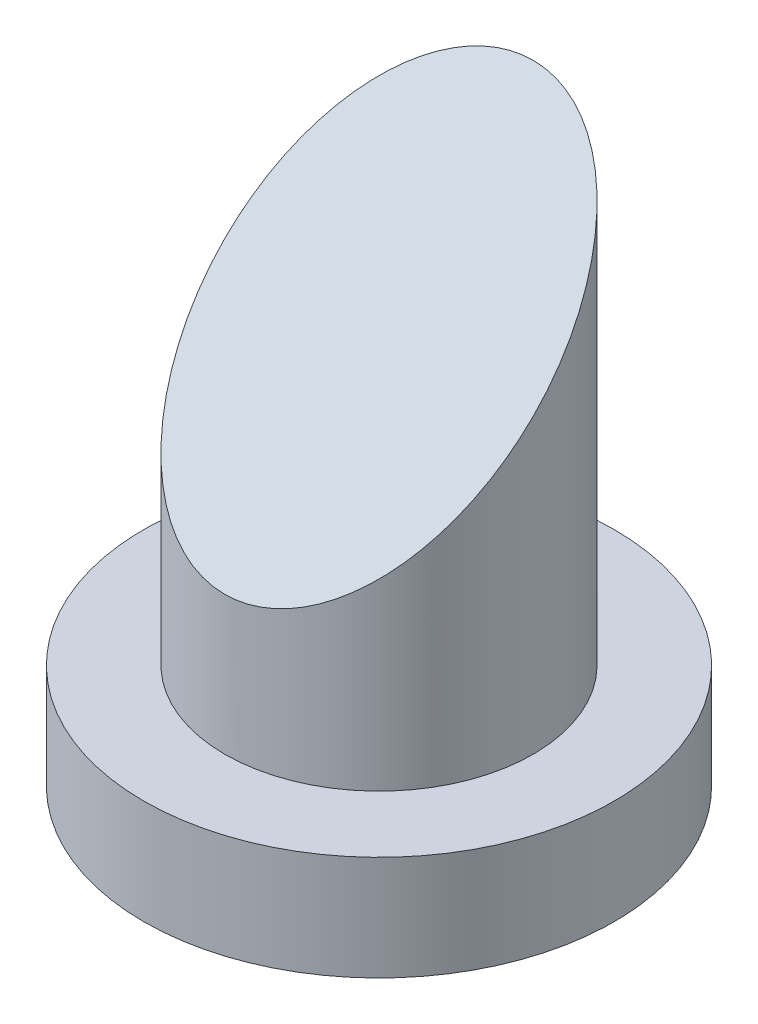
SolidWorks part; units mm, degrees
material "PTFE (general)"
ref_plane "Front Plane" through (0, 0, 0) normal (0, 0, 1) x (1, 0, 0)
ref_plane "Top Plane" through (0, 0, 0) normal (0, 1, 0) x (1, 0, 0)
ref_plane "Right Plane" through (0, 0, 0) normal (1, 0, 0) x (0, 0, -1)
sketch "Sketch1" plane through (0, 0, 0) normal (0, 1, 0) x (1, 0, 0)
  circle A0 centre (0, 0) radius 9
  dimension "D1" = 18
extrude "Boss-Extrude1" add sketch "Sketch1" along normal blind 4
sketch "Sketch2" plane through (0, 4, 0) normal (0, 1, 0) x (1, 0, 0)
  circle A0 centre (0, 0) radius 5.9
  dimension "D1" = 11.8
extrude "Boss-Extrude2" add sketch "Sketch2" along normal blind 20
sketch "Sketch3" plane through (0, 0, 0) normal (1, 0, 0) x (0, 0, -1)
  line L0 (-6.28, 8.92) -> (6.28, 21.48)
  line L2 (9, 4) -> (-9, 4) construction
  line L4 (-6.28, 8.92) -> (-6.28, 28.7719)
  line L5 (-6.28, 28.7719) -> (6.28, 28.7719)
  line L6 (6.28, 21.48) -> (6.28, 28.7719)
  point P2 (0, 15.2)
  dimension "D1" = 12.56
  dimension "D2" = 45
  dimension "D3" = 12.56
  dimension "D4" = 6.28
  dimension "D5" = 11.2
extrude "Cut-Extrude1" cut sketch "Sketch3" against normal through all both and the other way through all contours L0 L6 L5 L4
sketch "Sketch4" plane through (0, 0, 0) normal (0, -1, 0) x (1, 0, 0)
  circle A0 centre (0, -6) radius 0.425
  dimension "D1" = 0.85
  dimension "D2" = 6
extrude "Cut-Extrude2" cut sketch "Sketch4" against normal blind 1.5
